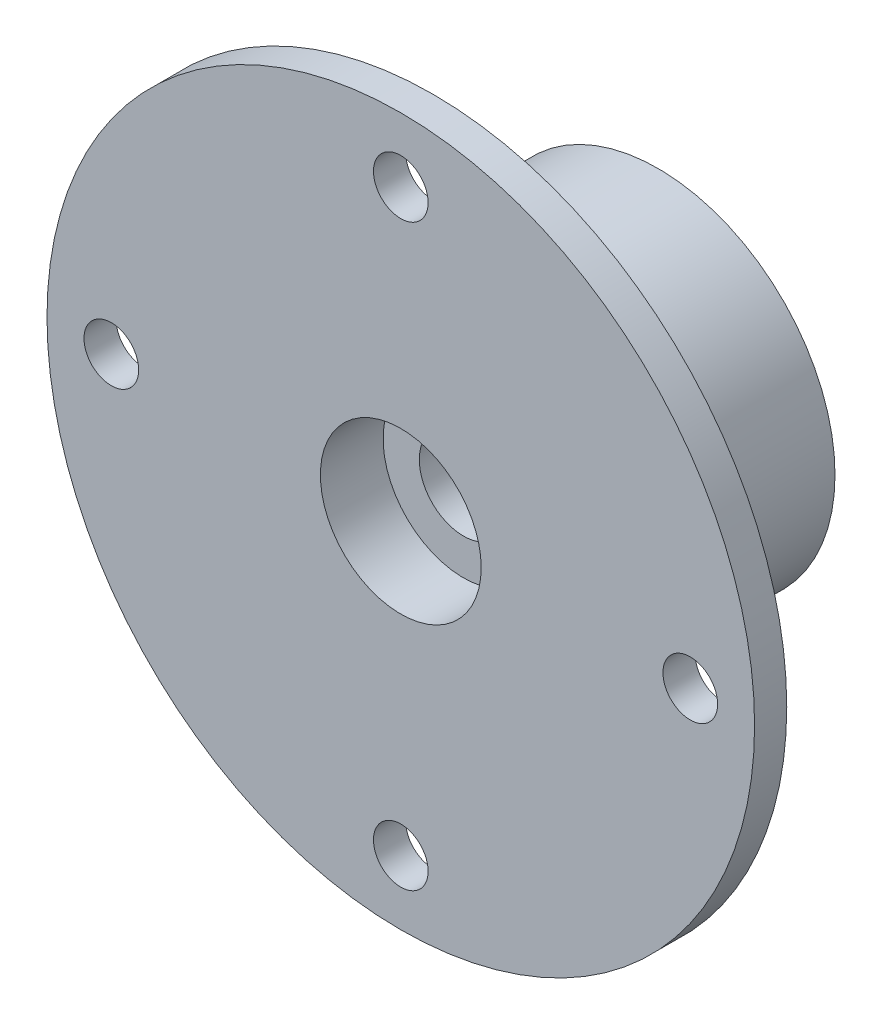
SolidWorks part; units mm, degrees
material "6061-T6 (SS)"
ref_plane "Front Plane" through (0, 0, 0) normal (0, 0, 1) x (1, 0, 0)
ref_plane "Top Plane" through (0, 0, 0) normal (0, 1, 0) x (1, 0, 0)
ref_plane "Right Plane" through (0, 0, 0) normal (1, 0, 0) x (0, 0, -1)
sketch "Sketch1" plane through (0, 0, 0) normal (0, 0, 1) x (1, 0, 0)
  circle A0 centre (0, 0) radius 11
  dimension "D1" = 22
extrude "Boss-Extrude1" add sketch "Sketch1" along normal blind 14
sketch "Sketch2" plane through (0, 0, 14) normal (0, 0, 1) x (1, 0, 0)
  circle A0 centre (0, 0) radius 22
  dimension "D1" = 44
extrude "Boss-Extrude2" add sketch "Sketch2" along normal blind 2
sketch "Sketch3" plane through (0, 0, 16) normal (0, 0, 1) x (1, 0, 0)
  circle A0 centre (0, 0) radius 18 construction
  point P4 (0, 18)
  point P9 (18, 0)
  point P10 (0, -18)
  point P11 (-18, 0)
  dimension "D1" = 36
  dimension "D2" = 4
hole_wizard "M3 Clearance Hole1" positions "Sketch3" profile "Sketch4" hole size "M3" standard "DIN" end condition through all
sketch "Sketch4" plane through (-18, 0, 16) normal (1, 0, 0) x (0, -1, 0)
  line L0 (0, 0) -> (0, 16)
  line L1 (0, 16) -> (1.7, 16)
  line L2 (1.7, 16) -> (1.7, 0)
  line L5 (1.7, 0) -> (0, 0)
  line L11 (0, -6.35) -> (0, 107.95) construction
  dimension "Thru Hole Dia." = 3.4
  dimension "Thru Hole Depth" = 16
sketch "Sketch5" plane through (0, 0, 16) normal (0, 0, 1) x (1, 0, 0)
  point P0 (0, 0)
hole_wizard "CBORE for M5 Hex Socket Thin Head Cap Screw1" positions "Sketch5" profile "Sketch6" counterbore size "M5" standard "DIN" end condition through all
sketch "Sketch6" plane through (0, 0, 16) normal (1, 0, 0) x (0, -1, 0)
  line L0 (0, 0) -> (0, 16)
  line L1 (0, 16) -> (2.75, 16)
  line L3 (2.75, 16) -> (2.75, 3.9)
  line L4 (2.75, 3.9) -> (5, 3.9)
  line L5 (5, 3.9) -> (5, 0)
  line L7 (5, 0) -> (0, 0)
  line L11 (0, -6.35) -> (0, 107.95) construction
  dimension "Thru Hole Dia." = 5.5
  dimension "Thru Hole Depth" = 16
  dimension "C'Bore Dia." = 10
  dimension "C'Bore Depth" = 3.9
fillet "Fillet1" radius 0.5 1 edges at (11, 0, 14)
